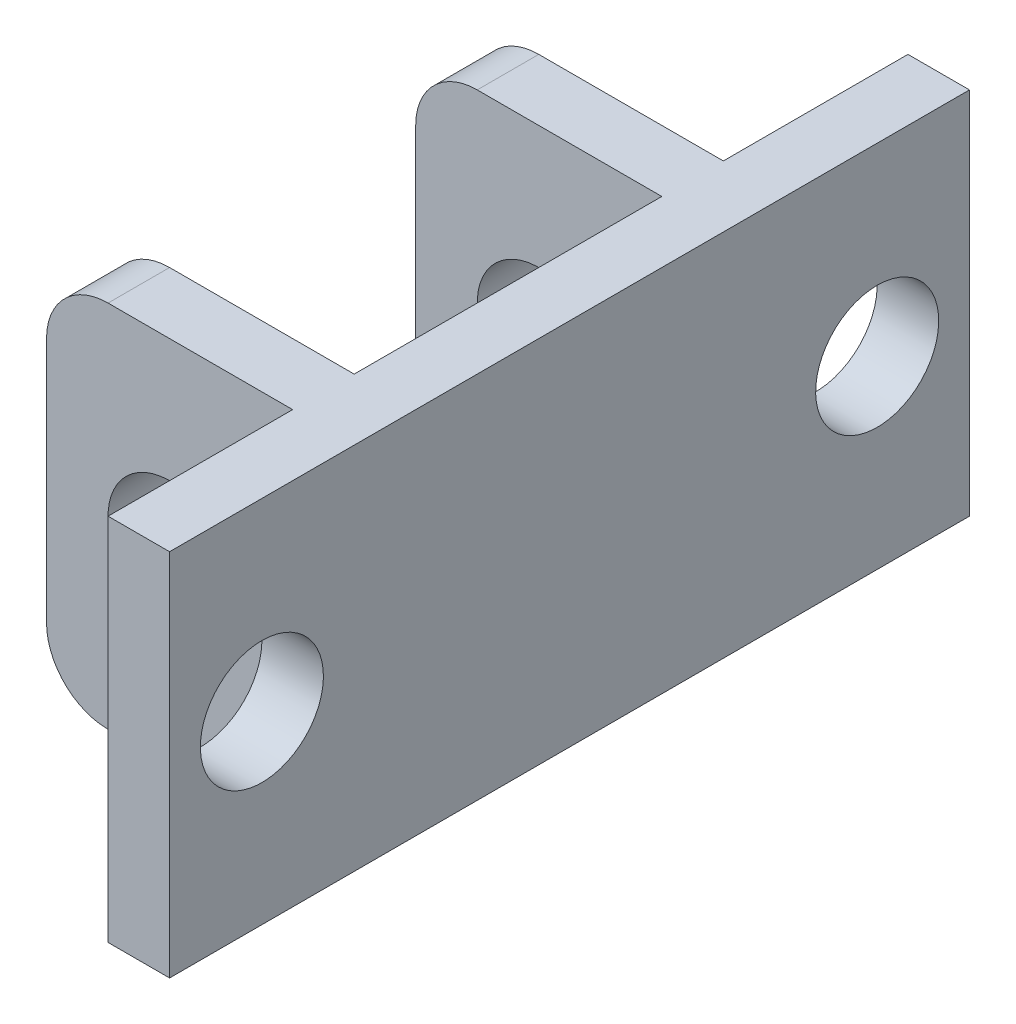
SolidWorks part; units mm, degrees
ref_plane "前视基准面" through (0, 0, 0) normal (0, 0, 1) x (1, 0, 0)
ref_plane "上视基准面" through (0, 0, 0) normal (0, 1, 0) x (1, 0, 0)
ref_plane "右视基准面" through (0, 0, 0) normal (1, 0, 0) x (0, 0, -1)
sketch "草图1" plane through (0, 0, 0) normal (0, 0, 1) x (1, 0, 0)
  line L1 (-2, 3) -> (2, 3)
  line L2 (-2, 3) -> (-2, -3)
  line L3 (-2, -3) -> (2, -3)
  line L4 (2, 3) -> (2, -3)
  line L5 (-2, 3) -> (2, -3) construction
  line L6 (-2, -3) -> (2, 3) construction
  circle A0 centre (0, 0) radius 1
  point P0 (0, 0)
  dimension "D3" = 2
  dimension "D1" = 4
  dimension "D2" = 6
extrude "凸台-拉伸1" add sketch "草图1" along normal blind 1
sketch "草图2" plane through (2, 0, 0) normal (1, 0, 0) x (0, 0, -1)
  line L0 (-4, 3) -> (-1, 3)
  line L1 (-4, 3) -> (-4, -3)
  line L2 (-4, -3) -> (-1, -3)
  line L3 (-1, -3) -> (-1, 3)
  line L4 (-1, 3) -> (2.5, 3)
  line L5 (-1, -3) -> (2.5, -3)
  line L6 (2.5, -3) -> (2.5, 3)
  circle A0 centre (-2.5, 0) radius 1
  line M6 (0, -3) -> (0, 3)
  line M7 (0, 3) -> (-1, 3)
  line M8 (-1, 3) -> (-1, -3)
  line M9 (-1, -3) -> (0, -3)
  dimension "D4" = 2
  dimension "D1" = 3
  dimension "D2" = 6
  dimension "D3" = 3.5
extrude "凸台-拉伸2" add sketch "草图2" along normal blind 1 contours L1 L2 L0 M8 | L5 L6 L4 M6 | M9 M6 M7 M8
fillet "圆角1" radius 1 2 edges at (-2, -3, 0.5) (-2, 3, 0.5)
mirror "镜向1" about plane through (3, 0, -2.5) normal (0, 0, 1) of bodies 107
